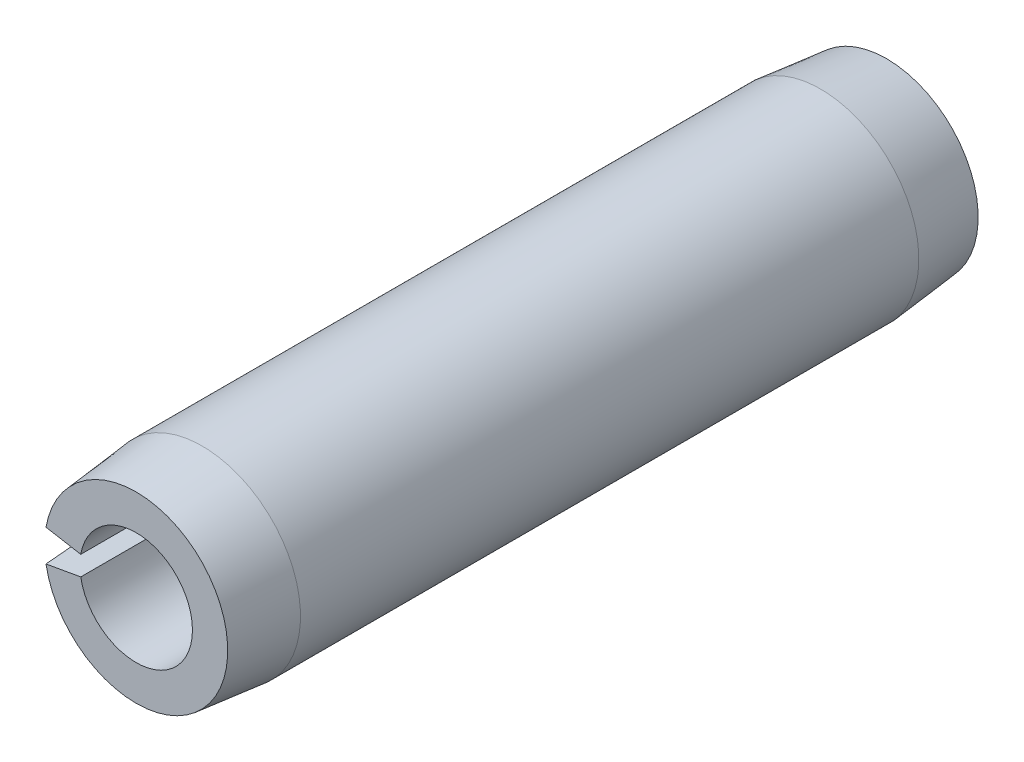
SolidWorks part; units mm, degrees
material "Plain Carbon Steel"
ref_plane "Front Plane" through (0, 0, 0) normal (0, 0, 1) x (1, 0, 0)
ref_plane "Top Plane" through (0, 0, 0) normal (0, 1, 0) x (1, 0, 0)
ref_plane "Right Plane" through (0, 0, 0) normal (1, 0, 0) x (0, 0, -1)
sketch "Sketch1" plane through (0, 0, 0) normal (0, 0, 1) x (1, 0, 0)
  line L0 (0.9525, 0) -> (1.6637, 0) construction
  line L1 (-1.6384, 0.2889) -> (-0.938, 0.1654)
  line L2 (-0.938, -0.1654) -> (-1.6384, -0.2889)
  arc A0 (-1.6384, -0.2889) -> (-1.6384, 0.2889) centre (0, 0) ccw
  arc A1 (-0.938, -0.1654) -> (-0.938, 0.1654) centre (0, 0) ccw
  dimension "OD" = 3.3274
  dimension "Wall thickness" = 0.7112
  dimension "D3" = 20
extrude "Extrude1" add sketch "Sketch1" along normal mid plane 12.7
sketch "Sketch2" plane through (0, 0, 0) normal (1, 0, 0) x (0, 0, -1)
  line L0 (0, -1.6637) -> (0, 1.6637) construction
  line L1 (6.35, 0) -> (-6.35, 0) construction
  line L2 (6.35, -0.9525) -> (6.35, 0.9525) construction
  line L3 (6.35, 1.6637) -> (-6.35, 1.6637) construction
  line L4 (6.35, 1.6637) -> (6.35, 1.5494)
  line L5 (6.35, 1.5494) -> (5.2324, 1.6637)
  line L6 (5.2324, 1.6637) -> (6.35, 1.6637)
  line L7 (6.35, -1.6637) -> (6.35, 1.6637) construction
  line L8 (-5.2324, 1.6637) -> (-6.35, 1.6637)
  line L9 (-6.35, 1.5494) -> (-5.2324, 1.6637)
  line L10 (-6.35, 1.6637) -> (-6.35, 1.5494)
  line L11 (5.2324, -1.6637) -> (6.35, -1.6637) construction
  line L12 (6.35, -1.5494) -> (5.2324, -1.6637) construction
  line L13 (6.35, -1.6637) -> (6.35, -1.5494) construction
  dimension "B" = 3.0988
  dimension "Chamfer max" = 1.1176
revolve "Cut-Revolve1" cut sketch "Sketch2" angle 360 about L1
sketch "Sketch3" plane through (0, 0, 0) normal (0, 0, 1) x (1, 0, 0)
  line L0 (0.9525, 0) -> (1.6637, 0) construction
  line L1 (0.9525, 0) -> (1.6637, 0)
  circle A0 centre (0, 0) radius 1.6637
  circle A1 centre (0, 0) radius 0.9525
  arc A2 (-1.6384, -0.2889) -> (-1.6384, 0.2889) centre (0, 0) ccw construction
  arc A3 (-0.938, -0.1654) -> (-0.938, 0.1654) centre (0, 0) ccw construction
